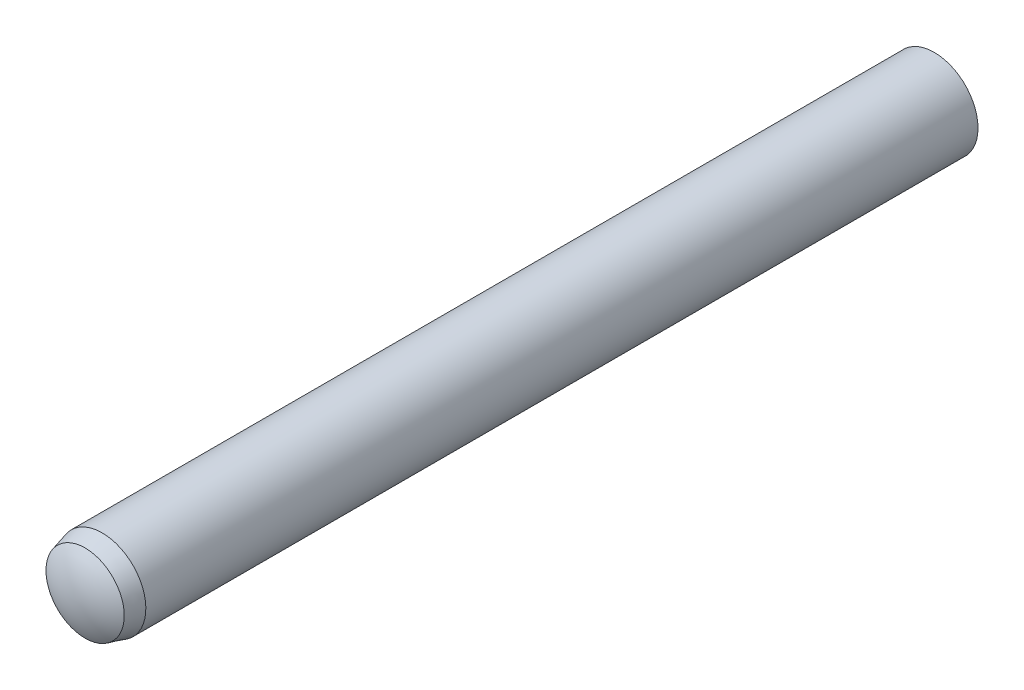
SolidWorks part; units mm, degrees
ref_plane "Front Plane" through (0, 0, 0) normal (0, 0, 1) x (1, 0, 0)
ref_plane "Top Plane" through (0, 0, 0) normal (0, 1, 0) x (1, 0, 0)
ref_plane "Right Plane" through (0, 0, 0) normal (1, 0, 0) x (0, 0, -1)
sketch "Sketch1" plane through (0, 0, 0) normal (0, 0, 1) x (1, 0, 0)
  circle A0 centre (0, 0) radius 5
  point P3 (0, 5)
  dimension "Diameter" = 10
sketch "Sketch2" plane through (0, 0, 0) normal (1, 0, 0) x (0, 0, -1)
  line L0 (-50, 0) -> (50, 0) construction
  line L1 (-50, 0) -> (-50, 5) construction
  line L2 (-50, 5) -> (50, 5)
  line L3 (50, 5) -> (50, 0) construction
  line L4 (-48.7, 4.4775) -> (-46.75, 5)
  arc A0 (-50, 0) -> (-48.7, 4.4775) centre (-41.6392, 0) cw
  arc A1 (50, 0) -> (48.5, 5) centre (40.9167, 0) ccw
  point P2 (0, 0)
  point P11 (-40, 0)
  point P13 (40, 0)
  dimension "Length" = 100
  dimension "D1" = 15
  dimension "D2" = 1.5
  dimension "D3" = 3.25
  dimension "D4" = 1.95
  dimension "D5" = 10
  dimension "D6" = 10
sketch "Sketch3" plane through (0, 0, 0) normal (1, 0, 0) x (0, 0, -1)
  line L0 (-50, 0) -> (50, 0) construction
  line L1 (-48.7, 4.4775) -> (-46.75, 5) construction
  line L2 (-50, 0) -> (50, 0)
  line L3 (-48.7, 4.4775) -> (-46.75, 5)
  line L4 (-46.75, 5) -> (48.5, 5)
  arc A0 (50, 0) -> (48.5, 5) centre (40.9167, 0) ccw construction
  arc A1 (-48.7, 4.4775) -> (-50, 0) centre (-41.6392, 0) ccw construction
  arc A2 (50, 0) -> (48.5, 5) centre (40.9167, 0) ccw
  arc A3 (-48.7, 4.4775) -> (-50, 0) centre (-41.6392, 0) ccw
revolve "Revolve1" add sketch "Sketch3" angle 360 about L2
equation "\"D2@Sketch2\" = \"Diameter@Sketch1\" * .15"
equation "\"D3@Sketch2\" = \"Diameter@Sketch1\" * .325"
equation "\"D4@Sketch2\" = \"D3@Sketch2\" * .6"
equation "\"D5@Sketch2\"=\"Diameter@Sketch1\""
equation "\"D6@Sketch2\"=\"D5@sketch2\""
